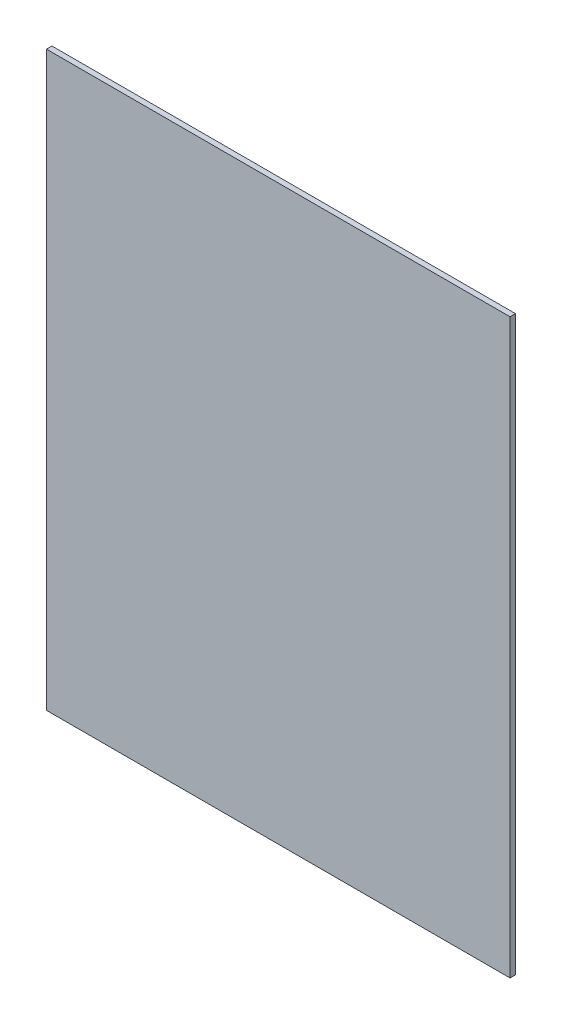
SolidWorks part; units mm, degrees
material "3003 Alloy"
ref_plane "Front Plane" through (0, 0, 0) normal (0, 0, 1) x (1, 0, 0)
ref_plane "Top Plane" through (0, 0, 0) normal (0, 1, 0) x (1, 0, 0)
ref_plane "Right Plane" through (0, 0, 0) normal (1, 0, 0) x (0, 0, -1)
sketch "Sketch1" plane through (0, 0, 0) normal (0, 0, 1) x (1, 0, 0)
  line L1 (85, -105) -> (-85, -105)
  line L2 (85, -105) -> (85, 105)
  line L3 (85, 105) -> (-85, 105)
  line L4 (-85, -105) -> (-85, 105)
  line L5 (85, -105) -> (-85, 105) construction
  line L6 (85, 105) -> (-85, -105) construction
  point P0 (0, 0)
  dimension "D1" = 210
  dimension "D2" = 170
extrude "Boss-Extrude1" add sketch "Sketch1" along normal blind 2
